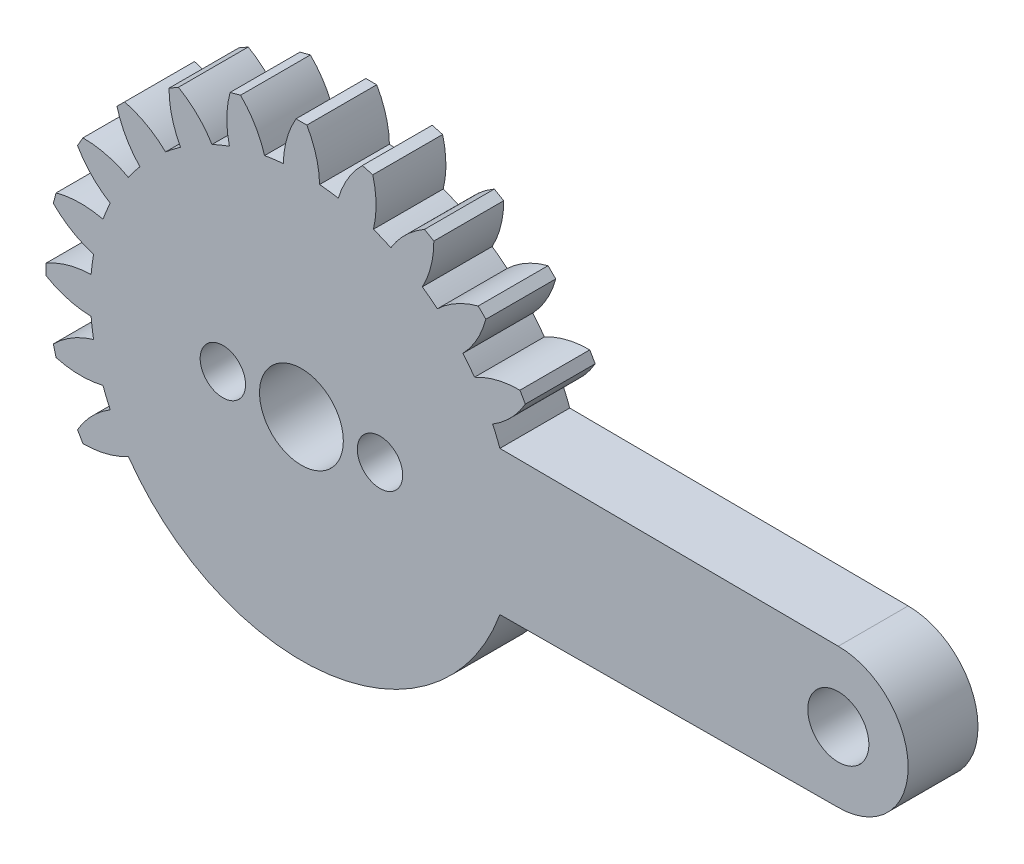
SolidWorks part; units mm, degrees
ref_plane "Front Plane" through (0, 0, 0) normal (0, 0, 1) x (1, 0, 0)
ref_plane "Top Plane" through (0, 0, 0) normal (0, 1, 0) x (1, 0, 0)
ref_plane "Right Plane" through (0, 0, 0) normal (1, 0, 0) x (0, 0, -1)
sketch "Sketch1" plane through (0, 0, 0) normal (0, 0, 1) x (1, 0, 0)
  line L0 (0, 0) -> (30.75, 0) construction
  line L1 (0, 14.63) -> (0, -14.63) construction
  line L2 (-0.31, 14.63) -> (0.31, 14.63)
  line L3 (3.4871, 14.2117) -> (4.086, 14.0513)
  line L4 (7.0465, 12.825) -> (7.5835, 12.515)
  line L5 (10.1258, 10.5642) -> (10.5642, 10.1258)
  line L6 (12.515, 7.5835) -> (12.825, 7.0465)
  line L7 (14.0513, 4.086) -> (14.2117, 3.4871)
  line L8 (14.63, 0.31) -> (14.63, -0.31)
  line L9 (14.2117, -3.4871) -> (14.0513, -4.086)
  line L10 (12.825, -7.0465) -> (12.515, -7.5835)
  line L11 (10.5642, -10.1258) -> (10.1258, -10.5642)
  line L12 (7.5835, -12.515) -> (7.0465, -12.825)
  line L13 (4.086, -14.0513) -> (3.4871, -14.2117)
  line L14 (0.31, -14.63) -> (-0.31, -14.63)
  line L15 (-3.4871, -14.2117) -> (-4.086, -14.0513)
  line L16 (-7.0465, -12.825) -> (-7.5835, -12.515)
  line L17 (-10.1258, -10.5642) -> (-10.5642, -10.1258)
  line L18 (-12.515, -7.5835) -> (-12.825, -7.0465)
  line L19 (-14.0513, -4.086) -> (-14.2117, -3.4871)
  line L20 (-14.63, -0.31) -> (-14.63, 0.31)
  line L21 (-14.2117, 3.4871) -> (-14.0513, 4.086)
  line L22 (-12.825, 7.0465) -> (-12.515, 7.5835)
  line L23 (-10.5642, 10.1258) -> (-10.1258, 10.5642)
  line L24 (-7.5835, 12.515) -> (-7.0465, 12.825)
  line L25 (-4.086, 14.0513) -> (-3.4871, 14.2117)
  line L26 (30.75, 0) -> (30.75, 4) construction
  line L27 (30.75, 0) -> (30.75, -4) construction
  line L28 (30.75, 4) -> (11.3656, 4.1221)
  line L29 (30.75, -4) -> (11.3656, -4.1221)
  circle A0 centre (0, 0) radius 12.09
  circle A1 centre (0, 0) radius 1.75
  circle A2 centre (30.75, 0) radius 1.75
  arc A3 (-1.04, 12.0452) -> (-0.31, 14.63) centre (4.3585, 11.9161) cw
  arc A4 (1.04, 12.0452) -> (0.31, 14.63) centre (-4.3585, 11.9161) ccw
  arc A5 (2.113, 11.9039) -> (3.4871, 14.2117) centre (7.294, 10.382) cw
  arc A6 (4.1221, 11.3656) -> (4.086, 14.0513) centre (-1.1258, 12.6381) ccw
  arc A7 (5.1219, 10.9514) -> (7.0465, 12.825) centre (9.7326, 8.1404) cw
  arc A8 (6.9233, 9.9114) -> (7.5835, 12.515) centre (2.1835, 12.4988) ccw
  arc A9 (7.7818, 9.2526) -> (10.1258, 10.5642) centre (11.5078, 5.344) cw
  arc A10 (9.2526, 7.7818) -> (10.5642, 10.1258) centre (5.344, 11.5078) ccw
  arc A11 (9.9114, 6.9233) -> (12.515, 7.5835) centre (12.4988, 2.1835) cw
  arc A12 (10.9514, 5.1219) -> (12.825, 7.0465) centre (8.1404, 9.7326) ccw
  arc A13 (11.3656, 4.1221) -> (14.0513, 4.086) centre (12.6381, -1.1258) cw
  arc A14 (11.9039, 2.113) -> (14.2117, 3.4871) centre (10.382, 7.294) ccw
  arc A15 (12.0452, 1.04) -> (14.63, 0.31) centre (11.9161, -4.3585) cw
  arc A16 (12.0452, -1.04) -> (14.63, -0.31) centre (11.9161, 4.3585) ccw
  arc A17 (11.9039, -2.113) -> (14.2117, -3.4871) centre (10.382, -7.294) cw
  arc A18 (11.3656, -4.1221) -> (14.0513, -4.086) centre (12.6381, 1.1258) ccw
  arc A19 (10.9514, -5.1219) -> (12.825, -7.0465) centre (8.1404, -9.7326) cw
  arc A20 (9.9114, -6.9233) -> (12.515, -7.5835) centre (12.4988, -2.1835) ccw
  arc A21 (9.2526, -7.7818) -> (10.5642, -10.1258) centre (5.344, -11.5078) cw
  arc A22 (7.7818, -9.2526) -> (10.1258, -10.5642) centre (11.5078, -5.344) ccw
  arc A23 (6.9233, -9.9114) -> (7.5835, -12.515) centre (2.1835, -12.4988) cw
  arc A24 (5.1219, -10.9514) -> (7.0465, -12.825) centre (9.7326, -8.1404) ccw
  arc A25 (4.1221, -11.3656) -> (4.086, -14.0513) centre (-1.1258, -12.6381) cw
  arc A26 (2.113, -11.9039) -> (3.4871, -14.2117) centre (7.294, -10.382) ccw
  arc A27 (1.04, -12.0452) -> (0.31, -14.63) centre (-4.3585, -11.9161) cw
  arc A28 (-1.04, -12.0452) -> (-0.31, -14.63) centre (4.3585, -11.9161) ccw
  arc A29 (-2.113, -11.9039) -> (-3.4871, -14.2117) centre (-7.294, -10.382) cw
  arc A30 (-4.1221, -11.3656) -> (-4.086, -14.0513) centre (1.1258, -12.6381) ccw
  arc A31 (-5.1219, -10.9514) -> (-7.0465, -12.825) centre (-9.7326, -8.1404) cw
  arc A32 (-6.9233, -9.9114) -> (-7.5835, -12.515) centre (-2.1835, -12.4988) ccw
  arc A33 (-7.7818, -9.2526) -> (-10.1258, -10.5642) centre (-11.5078, -5.344) cw
  arc A34 (-9.2526, -7.7818) -> (-10.5642, -10.1258) centre (-5.344, -11.5078) ccw
  arc A35 (-9.9114, -6.9233) -> (-12.515, -7.5835) centre (-12.4988, -2.1835) cw
  arc A36 (-10.9514, -5.1219) -> (-12.825, -7.0465) centre (-8.1404, -9.7326) ccw
  arc A37 (-11.3656, -4.1221) -> (-14.0513, -4.086) centre (-12.6381, 1.1258) cw
  arc A38 (-11.9039, -2.113) -> (-14.2117, -3.4871) centre (-10.382, -7.294) ccw
  arc A39 (-12.0452, -1.04) -> (-14.63, -0.31) centre (-11.9161, 4.3585) cw
  arc A40 (-12.0452, 1.04) -> (-14.63, 0.31) centre (-11.9161, -4.3585) ccw
  arc A41 (-11.9039, 2.113) -> (-14.2117, 3.4871) centre (-10.382, 7.294) cw
  arc A42 (-11.3656, 4.1221) -> (-14.0513, 4.086) centre (-12.6381, -1.1258) ccw
  arc A43 (-10.9514, 5.1219) -> (-12.825, 7.0465) centre (-8.1404, 9.7326) cw
  arc A44 (-9.9114, 6.9233) -> (-12.515, 7.5835) centre (-12.4988, 2.1835) ccw
  arc A45 (-9.2526, 7.7818) -> (-10.5642, 10.1258) centre (-5.344, 11.5078) cw
  arc A46 (-7.7818, 9.2526) -> (-10.1258, 10.5642) centre (-11.5078, 5.344) ccw
  arc A47 (-6.9233, 9.9114) -> (-7.5835, 12.515) centre (-2.1835, 12.4988) cw
  arc A48 (-5.1219, 10.9514) -> (-7.0465, 12.825) centre (-9.7326, 8.1404) ccw
  arc A49 (-4.1221, 11.3656) -> (-4.086, 14.0513) centre (1.1258, 12.6381) cw
  arc A50 (-2.113, 11.9039) -> (-3.4871, 14.2117) centre (-7.294, 10.382) ccw
  arc A51 (30.75, -4) -> (30.75, 4) centre (30.75, 0) ccw
  point P9 (0, 0)
  point P156 (0, 0)
  dimension "D2" = 3.5
  dimension "D3" = 3.5
  dimension "D4" = 24.18
  dimension "D6" = 5.4
  dimension "D10" = 8
  dimension "D1" = 30.75
  dimension "D5" = 29.26
  dimension "D7" = 0.31
  dimension "D8" = 1.04
  dimension "D9" = 24
extrude "Boss-Extrude1" add sketch "Sketch1" along normal blind 4 contours L29 A51 L28 A13 L7 A14 A0 A15 L8 A16 A17 L9 A18 A2 | A0 A50 L25 A49 | A0 A48 L24 A47 | A0 A46 L23 A45 | A0 A44 L22 A43 | A0 A42 L21 A41 | A0 A40 L20 A39 | A0 A38 L19 A37 | A0 A36 L18 A35 | A0 A4 L2 A3 | A0 A6 L3 A5 | A0 A8 L4 A7 | A0 A12 L6 A11 | A0 A10 L5 A9 | A0 A14 L7 A13 L28 | A0 A16 L8 A15 | L29 A18 L9 A17 A0 | A0 A1
sketch "Sketch2" plane through (0, 0, 4) normal (0, 0, 1) x (1, 0, 0)
  circle A0 centre (0, 0) radius 1.75
  dimension "D1" = 3.5
extrude "Cut-Extrude2" cut sketch "Sketch2" against normal through all
sketch "Sketch3" plane through (0, 0, 4) normal (0, 0, 1) x (1, 0, 0)
  line L0 (-4.5, 0) -> (4.5, 0) construction
  circle A0 centre (0, 0) radius 2.4
  circle A1 centre (-4.5, 0) radius 1.3
  circle A2 centre (4.5, 0) radius 1.3
  point P6 (0, 0)
  dimension "D2" = 2.6
  dimension "D3" = 2.6
  dimension "D4" = 4.8
  dimension "D1" = 9
extrude "Cut-Extrude3" cut sketch "Sketch3" against normal through all contours A1 | A0 | A2
